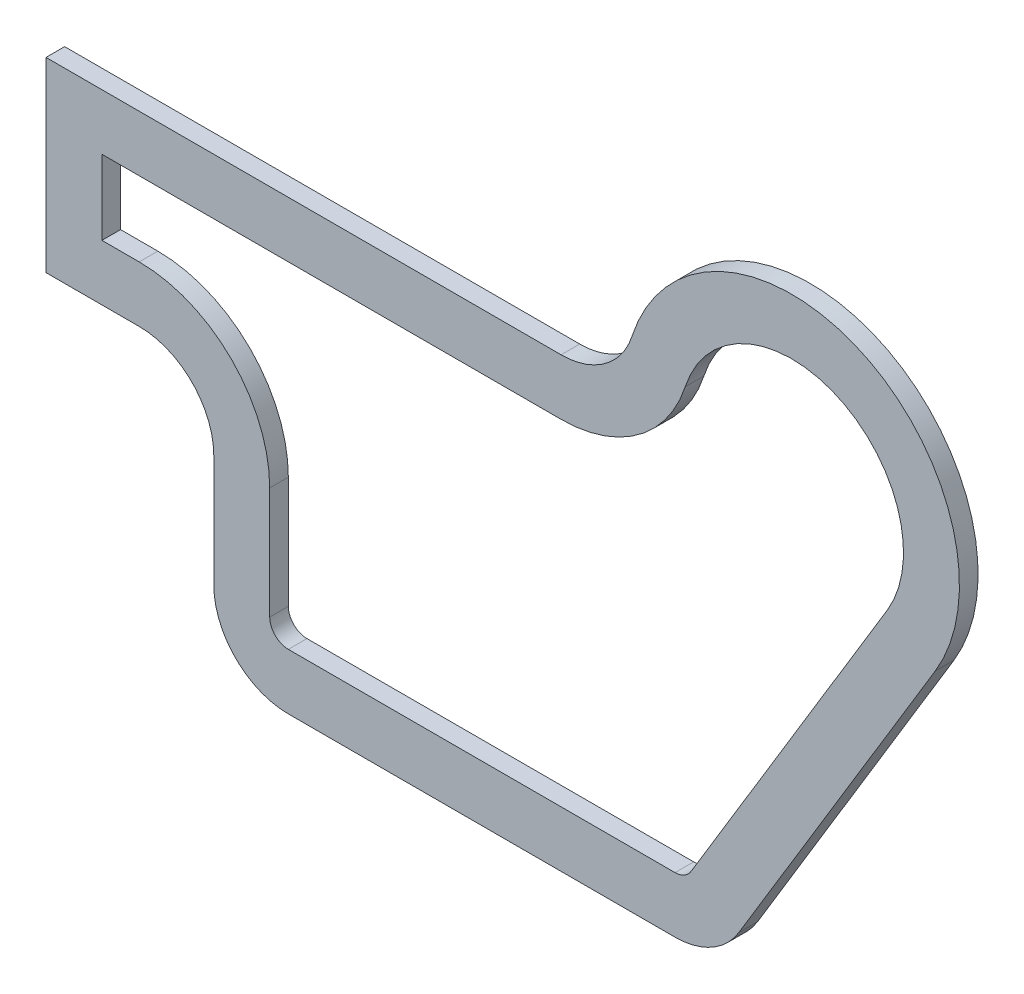
SolidWorks part; units mm, degrees
ref_plane "Front Plane" through (0, 0, 0) normal (0, 0, 1) x (1, 0, 0)
ref_plane "Top Plane" through (0, 0, 0) normal (0, 1, 0) x (1, 0, 0)
ref_plane "Right Plane" through (0, 0, 0) normal (1, 0, 0) x (0, 0, -1)
sketch "Sketch1" plane through (0, 0, 0) normal (0, 0, 1) x (1, 0, 0)
  line L0 (-45, 120) -> (-45, 70)
  line L1 (-45, 70) -> (-20, 70)
  line L2 (0, 50) -> (0, 20)
  line L3 (-45, 120) -> (93.1534, 120)
  line L4 (20, 0) -> (123.7241, 0)
  line L5 (140.8365, 9.6479) -> (193.5029, 96.7078)
  arc A0 (193.5029, 96.7078) -> (112.1831, 133.8462) centre (155, 120) ccw
  arc A1 (123.7241, 0) -> (140.8365, 9.6479) centre (123.7241, 20) ccw
  arc A2 (0, 20) -> (20, 0) centre (20, 20) ccw
  arc A3 (-20, 70) -> (0, 50) centre (-20, 50) cw
  arc A4 (93.1534, 120) -> (112.1831, 133.8462) centre (93.1534, 140) ccw
  point P8 (0, 0)
  point P9 (-175.9269, 78.954)
  point P10 (-126.176, -55.5577)
  point P11 (0, 0)
  point P15 (135, 0)
  point P18 (0, 0)
  dimension "D4" = 45
  dimension "D7" = 20
  dimension "D1" = 200
  dimension "D2" = 50
  dimension "D3" = 180
  dimension "D5" = 120
  dimension "D6" = 45
extrude "base " add sketch "Sketch1" along normal blind 5
sketch "Sketch2" plane through (0, 0, 5) normal (0, 0, 1) x (1, 0, 0)
  line L0 (93.1534, 105) -> (-30, 105)
  line L1 (-30, 105) -> (-30, 85)
  line L2 (-30, 85) -> (-20, 85)
  line L3 (15, 50) -> (15, 20)
  line L4 (20, 15) -> (123.7241, 15)
  line L5 (128.0022, 17.412) -> (180.6686, 104.4719)
  line L6 (93.1534, 120) -> (-45, 120)
  line L7 (-45, 120) -> (-45, 70)
  line L8 (-45, 70) -> (-20, 70)
  line L9 (0, 50) -> (0, 20)
  line L10 (20, 0) -> (123.7241, 0)
  line L11 (140.8365, 9.6479) -> (193.5029, 96.7078)
  line L12 (93.1534, 120) -> (-45, 120) construction
  line L13 (-45, 120) -> (-45, 70) construction
  line L14 (-45, 70) -> (-20, 70) construction
  line L15 (0, 50) -> (0, 20) construction
  line L16 (20, 0) -> (123.7241, 0) construction
  line L17 (140.8365, 9.6479) -> (193.5029, 96.7078) construction
  arc A0 (15, 50) -> (-20, 85) centre (-20, 50) ccw
  arc A1 (15, 20) -> (20, 15) centre (20, 20) ccw
  arc A2 (123.7241, 15) -> (128.0022, 17.412) centre (123.7241, 20) ccw
  arc A3 (180.6686, 104.4719) -> (126.4554, 129.2308) centre (155, 120) ccw
  arc A4 (93.1534, 105) -> (126.4554, 129.2308) centre (93.1534, 140) ccw
  arc A5 (0, 50) -> (-20, 70) centre (-20, 50) ccw
  arc A6 (0, 20) -> (20, 0) centre (20, 20) ccw
  arc A7 (123.7241, 0) -> (140.8365, 9.6479) centre (123.7241, 20) ccw
  arc A8 (193.5029, 96.7078) -> (112.1831, 133.8462) centre (155, 120) ccw
  arc A9 (93.1534, 120) -> (112.1831, 133.8462) centre (93.1534, 140) ccw
  arc A10 (0, 50) -> (-20, 70) centre (-20, 50) ccw construction
  arc A11 (0, 20) -> (20, 0) centre (20, 20) ccw construction
  arc A12 (123.7241, 0) -> (140.8365, 9.6479) centre (123.7241, 20) ccw construction
  arc A13 (193.5029, 96.7078) -> (112.1831, 133.8462) centre (155, 120) ccw construction
  arc A14 (93.1534, 120) -> (112.1831, 133.8462) centre (93.1534, 140) ccw construction
  dimension "D1" = 0
  dimension "D2" = 15
extrude "Cut-Extrude1" cut sketch "Sketch2" against normal through all
